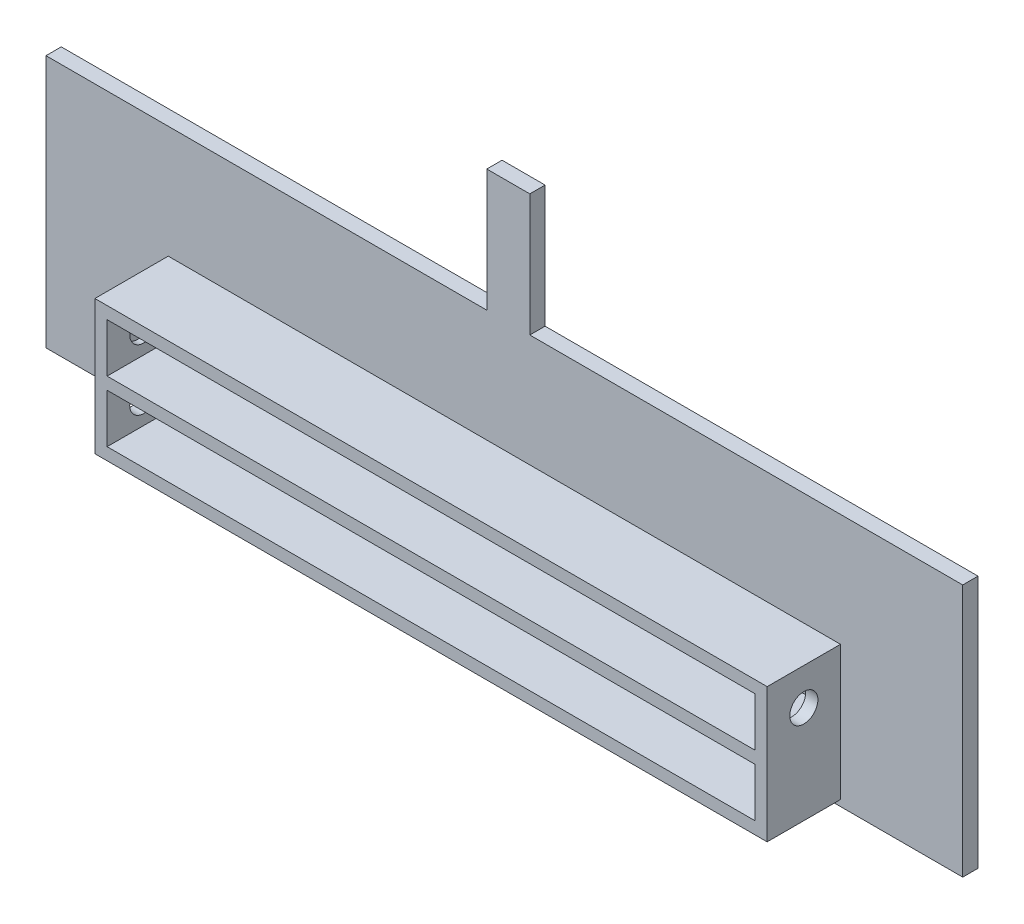
SolidWorks part; units mm, degrees
ref_plane "Front Plane" through (0, 0, 0) normal (0, 0, 1) x (1, 0, 0)
ref_plane "Top Plane" through (0, 0, 0) normal (0, 1, 0) x (1, 0, 0)
ref_plane "Right Plane" through (0, 0, 0) normal (1, 0, 0) x (0, 0, -1)
sketch "Sketch1" plane through (0, 0, 0) normal (0, 0, 1) x (1, 0, 0)
  line L1 (-75, 29.41) -> (75, 29.41)
  line L2 (-75, 29.41) -> (-75, -12)
  line L3 (-75, -12) -> (75, -12)
  line L4 (75, 29.41) -> (75, -12)
  point P4 (0, -12)
  dimension "D1" = 150
  dimension "D2" = 41.41
extrude "Boss-Extrude1" add sketch "Sketch1" along normal blind 2.5
sketch "Sketch5" plane through (0, 0, 2.5) normal (0, 0, 1) x (1, 0, 0)
  line L1 (-55, 11) -> (55, 11)
  line L2 (-55, 11) -> (-55, -11)
  line L3 (-55, -11) -> (55, -11)
  line L4 (55, 11) -> (55, -11)
  point P4 (55, 0)
  point P7 (0, -11)
  dimension "D1" = 110
  dimension "D2" = 22
extrude "Boss-Extrude3" add sketch "Sketch5" along normal blind 12
sketch "Sketch6" plane through (0, 0, 2.5) normal (0, 0, 1) x (1, 0, 0)
  line L1 (-53, 9) -> (53, 9)
  line L2 (-53, 9) -> (-53, 1)
  line L3 (-53, 1) -> (53, 1)
  line L4 (53, 9) -> (53, 1)
  line L5 (-53, -1) -> (53, -1)
  line L6 (-53, -1) -> (-53, -9)
  line L7 (-53, -9) -> (53, -9)
  line L8 (53, -1) -> (53, -9)
  point P8 (0, 9)
  point P9 (0, -9)
  dimension "D1" = 106
  dimension "D2" = 106
  dimension "D3" = 8
  dimension "D4" = 8
  dimension "D5" = 1
  dimension "D6" = 1
extrude "Cut-Extrude3" cut sketch "Sketch6" along normal blind 12
sketch "Sketch7" plane through (-55, 0, 0) normal (-1, 0, 0) x (0, 0, 1)
  line L0 (14.5, -11) -> (2.5, -11) construction
  line L2 (14.5, 11) -> (14.5, -11) construction
  circle A0 centre (8.5, -5) radius 2.3
  dimension "D1" = 4.6
  dimension "D2" = 6
  dimension "D3" = 6
extrude "Cut-Extrude4" cut sketch "Sketch7" against normal blind 109
sketch "Sketch8" plane through (55, 0, 0) normal (1, 0, 0) x (0, 0, -1)
  line L0 (-14.5, 11) -> (-2.5, 11) construction
  line L1 (-14.5, -11) -> (-14.5, 11) construction
  circle A0 centre (-8.5, 5) radius 2.3
  dimension "D1" = 4.6
  dimension "D2" = 6
  dimension "D3" = 6
extrude "Cut-Extrude5" cut sketch "Sketch8" against normal blind 109
sketch "Sketch9" plane through (0, 29.41, 0) normal (0, 1, 0) x (1, 0, 0)
  line L0 (75, 0) -> (-75, 0) construction
  line L1 (-2.8748, 0) -> (4.1652, 0)
  line L2 (-2.8748, 0) -> (-2.8748, -2.5)
  line L3 (-2.8748, -2.5) -> (4.1652, -2.5)
  line L4 (4.1652, 0) -> (4.1652, -2.5)
  line L5 (75, -2.5) -> (-75, -2.5) construction
extrude "Boss-Extrude4" add sketch "Sketch9" along normal blind 20
